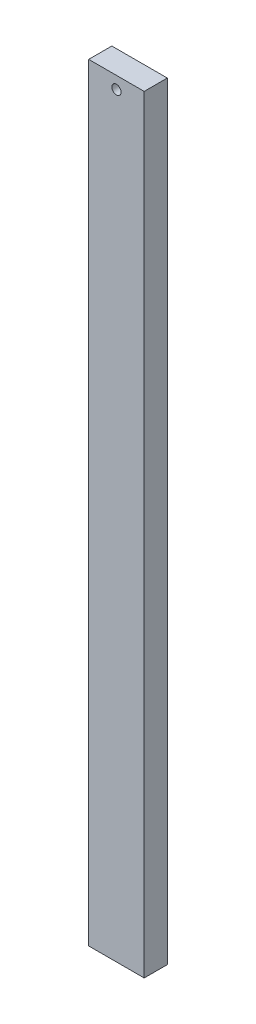
SolidWorks part; units mm, degrees
ref_plane "前视基准面" through (0, 0, 0) normal (0, 0, 1) x (1, 0, 0)
ref_plane "上视基准面" through (0, 0, 0) normal (0, 1, 0) x (1, 0, 0)
ref_plane "右视基准面" through (0, 0, 0) normal (1, 0, 0) x (0, 0, -1)
other "Configuration Table"
sketch "草图1" plane through (0, 0, 0) normal (0, 1, 0) x (1, 0, 0)
  line L1 (-18, 7.5) -> (18, 7.5)
  line L2 (-18, 7.5) -> (-18, -7.5)
  line L3 (-18, -7.5) -> (18, -7.5)
  line L4 (18, 7.5) -> (18, -7.5)
  line L5 (0, -7.5) -> (0, 7.5) construction
  line L6 (-18, 0) -> (18, 0) construction
  point P0 (0, 0)
  dimension "D1" = 36
  dimension "D2" = 15
extrude "凸台-拉伸1" add sketch "草图1" along normal blind 498.33
sketch "草图2" plane through (0, 0, 7.5) normal (0, 0, 1) x (1, 0, 0)
  line L0 (-18, 498.33) -> (18, 498.33) construction
  line L1 (-18, 498.33) -> (-18, 0) construction
  circle A0 centre (0, 490.33) radius 3
  dimension "D1" = 6
  dimension "D2" = 8
  dimension "D3" = 18
extrude "切除-拉伸1" cut sketch "草图2" against normal through all
